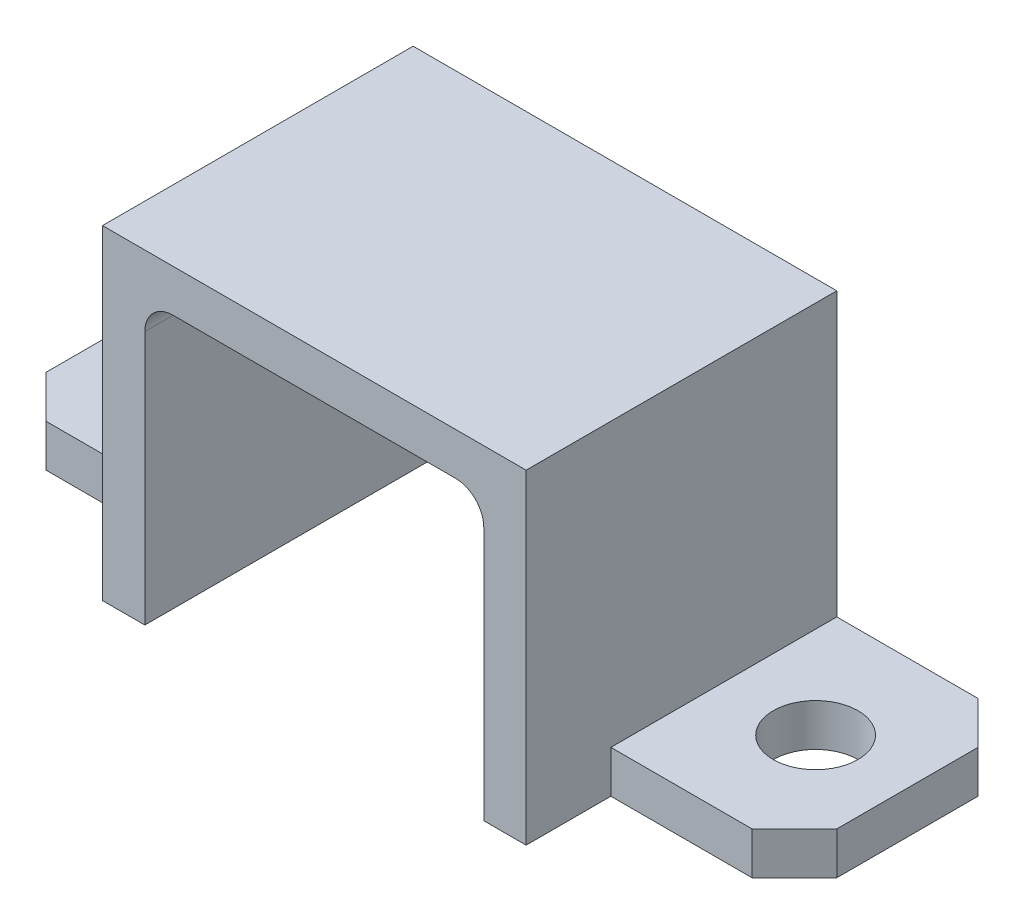
SolidWorks part; units mm, degrees
ref_plane "Front Plane" through (0, 0, 0) normal (0, 0, 1) x (1, 0, 0)
ref_plane "Top Plane" through (0, 0, 0) normal (0, 1, 0) x (1, 0, 0)
ref_plane "Right Plane" through (0, 0, 0) normal (1, 0, 0) x (0, 0, -1)
sketch "Sketch1" plane through (0, 0, 0) normal (0, 0, 1) x (1, 0, 0)
  line L0 (0.5, 1.5) -> (0.5, 11.5)
  line L1 (0.5, 11.5) -> (15.5, 11.5)
  line L2 (15.5, 11.5) -> (15.5, 1.5)
  line L3 (2, 0) -> (2, 9)
  line L4 (3, 10) -> (13, 10)
  line L5 (14, 9) -> (14, 0)
  line L6 (14, 0) -> (22, 0)
  line L7 (22, 0) -> (22, 1.5)
  line L8 (22, 1.5) -> (15.5, 1.5)
  line L9 (2, 0) -> (-6, 0)
  line L10 (-6, 0) -> (-6, 1.5)
  line L11 (-6, 1.5) -> (0.5, 1.5)
  arc A0 (13, 10) -> (14, 9) centre (13, 9) cw
  arc A1 (2, 9) -> (3, 10) centre (3, 9) cw
  point P10 (14, 10)
  point P18 (2, 10)
  dimension "D1" = 1
  dimension "D2" = 15
  dimension "D3" = 1.5
  dimension "D4" = 10
  dimension "D5" = 10
  dimension "D6" = 1.5
  dimension "D7" = 1.5
  dimension "D8" = 6.5
  dimension "D9" = 6.5
  dimension "D10" = 1.5
extrude "Boss-Extrude1" add sketch "Sketch1" along normal blind 11
sketch "Sketch3" plane through (0, 0, 11) normal (0, 0, 1) x (1, 0, 0)
  line L1 (0.5, 1.5) -> (-6, 1.5)
  line L2 (0.5, 1.5) -> (0.5, 0)
  line L3 (0.5, 0) -> (-6, 0)
  line L4 (-6, 1.5) -> (-6, 0)
  line L5 (15.5, 1.5) -> (22, 1.5)
  line L6 (15.5, 1.5) -> (15.5, 0)
  line L7 (15.5, 0) -> (22, 0)
  line L8 (22, 1.5) -> (22, 0)
extrude "Cut-Extrude5" cut sketch "Sketch3" against normal blind 3
sketch "Sketch6" plane through (0, 1.5, 0) normal (0, 1, 0) x (1, 0, 0)
  line L0 (8, 0) -> (8, -1.6612) construction
  line L1 (15.5, 0) -> (0.5, 0) construction
  line L2 (-6, -1.5) -> (-4.5, 0)
  line L3 (-6, -8) -> (-6, 0) construction
  line L4 (0.5, 0) -> (-6, 0) construction
  line L5 (-4.5, 0) -> (-6, 0)
  line L6 (-6, 0) -> (-6, -1.5)
  line L7 (-6, -4) -> (3.2683, -4) construction
  line L8 (20.5, 0) -> (22, 0)
  line L9 (22, -1.5) -> (20.5, 0)
  line L10 (22, 0) -> (22, -1.5)
  line L11 (22, -6.5) -> (20.5, -8)
  line L12 (22, -8) -> (22, -6.5)
  line L13 (20.5, -8) -> (22, -8)
  line L14 (-4.5, -8) -> (-6, -8)
  line L15 (-6, -6.5) -> (-4.5, -8)
  line L16 (-6, -8) -> (-6, -6.5)
  circle A0 centre (-2.75, -4) radius 1.5
  circle A1 centre (18.75, -4) radius 1.5
  circle A2 centre (-2.75, -4) radius 2.65 construction
  circle A3 centre (18.75, -4) radius 2.65 construction
  dimension "D1" = 3
  dimension "D2" = 5.3
  dimension "D3" = 5.3
  dimension "D4" = 1.5
  dimension "D5" = 1.5
extrude "Cut-Extrude7" cut sketch "Sketch6" against normal through all
